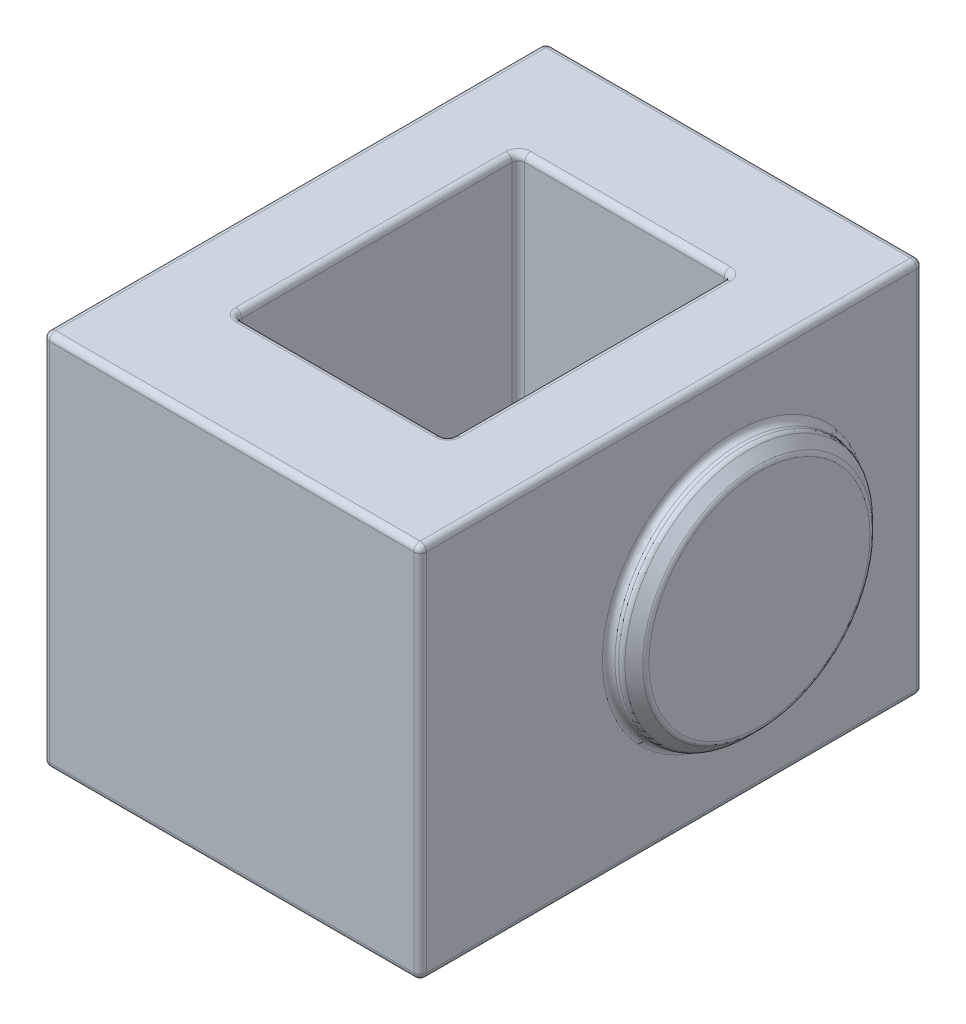
SolidWorks part; units mm, degrees
ref_plane "Front Plane" through (0, 0, 0) normal (0, 0, 1) x (1, 0, 0)
ref_plane "Top Plane" through (0, 0, 0) normal (0, 1, 0) x (1, 0, 0)
ref_plane "Right Plane" through (0, 0, 0) normal (1, 0, 0) x (0, 0, -1)
sketch "Sketch1" plane through (0, 0, 0) normal (0, 1, 0) x (1, 0, 0)
  line L1 (-30, -40) -> (30, -40)
  line L2 (-30, -40) -> (-30, 40)
  line L3 (-30, 40) -> (30, 40)
  line L4 (30, -40) -> (30, 40)
  line L5 (-30, -40) -> (30, 40) construction
  line L6 (-30, 40) -> (30, -40) construction
  line L7 (-16.875, -22.5) -> (16.875, -22.5)
  line L8 (-16.875, -22.5) -> (-16.875, 22.5)
  line L9 (-16.875, 22.5) -> (16.875, 22.5)
  line L10 (16.875, -22.5) -> (16.875, 22.5)
  line L11 (-16.875, -22.5) -> (16.875, 22.5) construction
  line L12 (-16.875, 22.5) -> (16.875, -22.5) construction
  point P0 (0, 0)
  point P6 (0, 0)
  dimension "D1" = 80
  dimension "D2" = 60
  dimension "D3" = 45
extrude "Boss-Extrude1" add sketch "Sketch1" along normal blind 60
sketch "Sketch2" plane through (30, 0, 0) normal (1, 0, 0) x (0, 0, -1)
  line L1 (40, 60) -> (40, 0) construction
  circle A0 centre (10, 30) radius 20
  dimension "D1" = 40
  dimension "D2" = 10
extrude "Boss-Extrude2" add sketch "Sketch2" along normal blind 4 contours A0
chamfer "Chamfer1" distance 2 angle 45 1 edges at (34, 30, -30)
fillet "Fillet1" radius 1 27 edges at (16.875, 0, 0) (0, 0, -22.5) (-16.875, 0, 0) (0, 0, 22.5) (16.875, 60, 0) (0, 60, -22.5) (-16.875, 60, 0) (0, 60, 22.5) (16.875, 30, 22.5) (-16.875, 30, 22.5) (-16.875, 30, -22.5) (16.875, 30, -22.5) (30, 0, 0) (0, 0, -40) (-30, 0, 0) (0, 0, 40) (30, 60, 0) (0, 60, -40) (-30, 60, 0) (0, 60, 40) (30, 30, 40) (-30, 30, 40) (-30, 30, -40) (30, 30, -40) (30, 30, -30) (34, 30, -28) (32, 30, -30)
